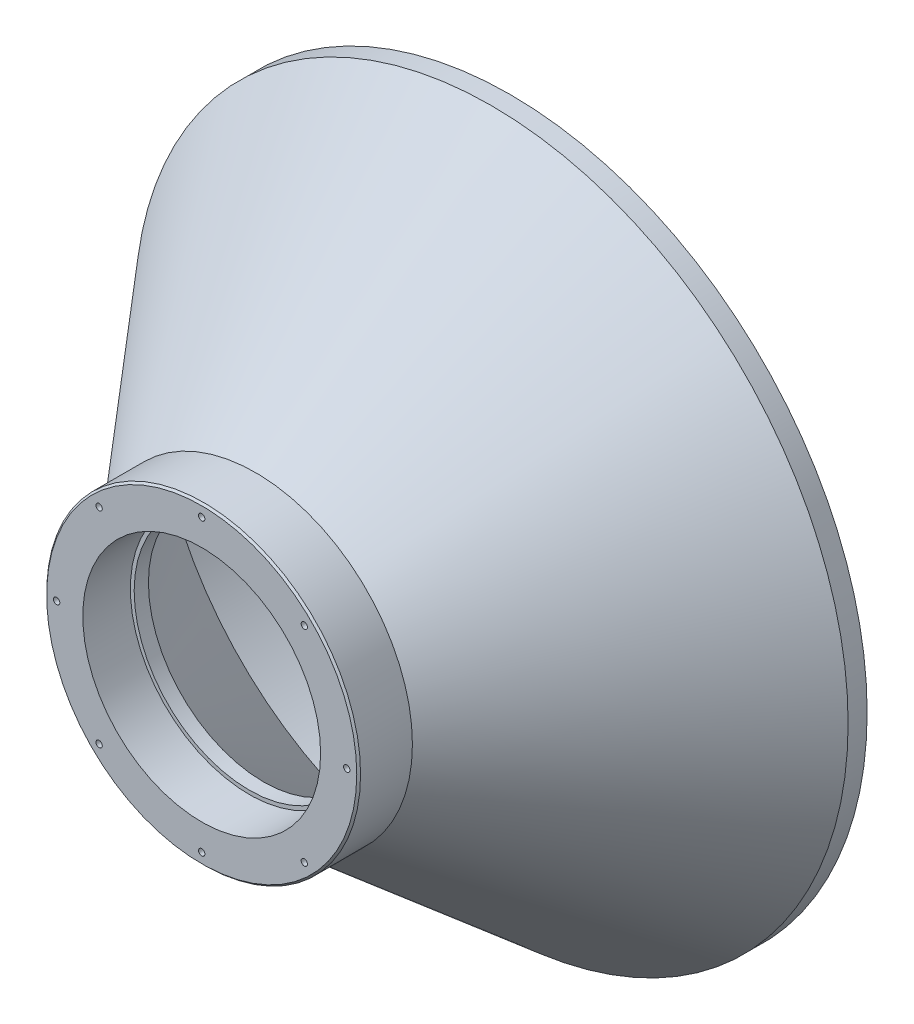
SolidWorks part; units mm, degrees
ref_plane "Front Plane" through (0, 0, 0) normal (0, 0, 1) x (1, 0, 0)
ref_plane "Top Plane" through (0, 0, 0) normal (0, 1, 0) x (1, 0, 0)
ref_plane "Right Plane" through (0, 0, 0) normal (1, 0, 0) x (0, 0, -1)
sketch "Sketch1" plane through (0, 0, 0) normal (0, 1, 0) x (1, 0, 0)
  line L0 (375, 4.5) -> (0, 4.5)
  line L1 (0, 4.5) -> (0, -320)
  line L2 (0, -320) -> (165, -320)
  line L3 (165, -320) -> (165, -263.511)
  line L4 (165, -263.511) -> (375, -15.5)
  line L5 (375, -15.5) -> (375, 4.5)
  line L6 (0, 4.5) -> (0, -320) construction
revolve "Revolve1" add sketch "Sketch1" angle 360 about L6
sketch "Sketch2" plane through (0, 0, 0) normal (0, 1, 0) x (1, 0, 0)
  line L0 (315, 4.5) -> (0, 4.5)
  line L1 (0, 4.5) -> (0, -320)
  line L2 (0, -320) -> (125, -320)
  line L3 (125, -320) -> (125, -270)
  line L4 (125, -270) -> (121, -270)
  line L5 (121, -270) -> (121, -255)
  line L6 (121, -255) -> (146, -255)
  line L7 (146, -255) -> (315, -55.4102)
  line L8 (315, -55.4102) -> (315, 4.5)
  line L9 (0, 4.5) -> (0, -320) construction
revolve "Cut-Revolve1" cut sketch "Sketch2" angle 360 about L9
hole_wizard "Hole1" positions "Sketch4" profile "Sketch3" legacy
sketch "Sketch4" plane through (0, 0, -4.5) normal (0, 0, -1) x (-1, 0, 0)
  point P0 (314.119, -130.1124)
  point P1 (-314.119, 130.1124)
sketch "Sketch3" plane through (-314.119, -130.1124, -4.5) normal (1, 0, 0) x (0, 1, 0)
  line L0 (0, 0) -> (0, 10)
  line L1 (0, 10) -> (4, 10)
  line L2 (4, 10) -> (4, 0)
  line L3 (4, 0) -> (0, 0)
  line L4 (0, 110) -> (0, -10) construction
  dimension "Diameter" = 8
  dimension "Depth" = 10
hole_wizard "5/16 Clearance Hole1" positions "Sketch6" profile "Sketch5" hole size "5/16" standard "ANSI Inch"
sketch "Sketch6" plane through (0, 0, -4.5) normal (0, 0, -1) x (-1, 0, 0)
  point P0 (0, -345)
  point P1 (-172.5, -298.7788)
  point P2 (-298.7788, -172.5)
  point P3 (-345, 0)
  point P4 (-298.7788, 172.5)
  point P5 (-172.5, 298.7788)
  point P6 (0, 345)
  point P7 (172.5, 298.7788)
  point P8 (298.7788, 172.5)
  point P9 (345, 0)
  point P10 (298.7788, -172.5)
  point P11 (172.5, -298.7788)
sketch "Sketch5" plane through (0, -345, -4.5) normal (1, 0, 0) x (0, 1, 0)
  line L0 (0, 0) -> (0, 25.5164)
  line L1 (0, 25.5164) -> (4.188, 23)
  line L2 (4.188, 23) -> (4.188, 0)
  line L5 (4.188, 0) -> (0, 0)
  line L10 (0, 25.5164) -> (-4.188, 23) construction
  line L11 (0, -6.35) -> (0, 107.95) construction
  dimension "Hole Dia." = 8.376
  dimension "Hole Depth" = 23
  dimension "Drill Angle" = 118
hole_wizard "1/4 Clearance Hole1" positions "Sketch8" profile "Sketch7" hole size "1/4" standard "ANSI Inch"
sketch "Sketch8" plane through (0, 0, 320) normal (0, 0, 1) x (1, 0, 0)
  point P0 (-107.8338, 107.8338)
  point P1 (0, 152.5)
  point P2 (107.8338, 107.8338)
  point P3 (152.5, 0)
  point P4 (107.8338, -107.8338)
  point P5 (0, -152.5)
  point P6 (-107.8338, -107.8338)
  point P7 (-152.5, 0)
sketch "Sketch7" plane through (-107.8338, 107.8338, 320) normal (1, 0, 0) x (0, -1, 0)
  line L0 (0, 0) -> (0, 21.997)
  line L1 (0, 21.997) -> (3.3235, 20)
  line L2 (3.3235, 20) -> (3.3235, 0)
  line L5 (3.3235, 0) -> (0, 0)
  line L10 (0, 21.997) -> (-3.3235, 20) construction
  line L11 (0, -6.35) -> (0, 107.95) construction
  dimension "Hole Dia." = 6.647
  dimension "Hole Depth" = 20
  dimension "Drill Angle" = 118
chamfer "Chamfer1" distance 0.5 angle 45 10 edges at (-176.688, 298.7788, -4.5) (168.312, 298.7788, -4.5) (-4.188, 345, -4.5) (294.5908, -172.5, -4.5) (-4.188, -345, -4.5) (310.119, 130.1124, -4.5) (-318.119, -130.1124, -4.5) (340.812, 0, -4.5) (168.312, -298.7788, -4.5) (294.5908, 172.5, -4.5)
chamfer "Chamfer6" distance 2 angle 45 1 edges at (315, 0, -4.5)
chamfer "Chamfer7" distance 2 angle 45 1 edges at (165, 0, 320)
